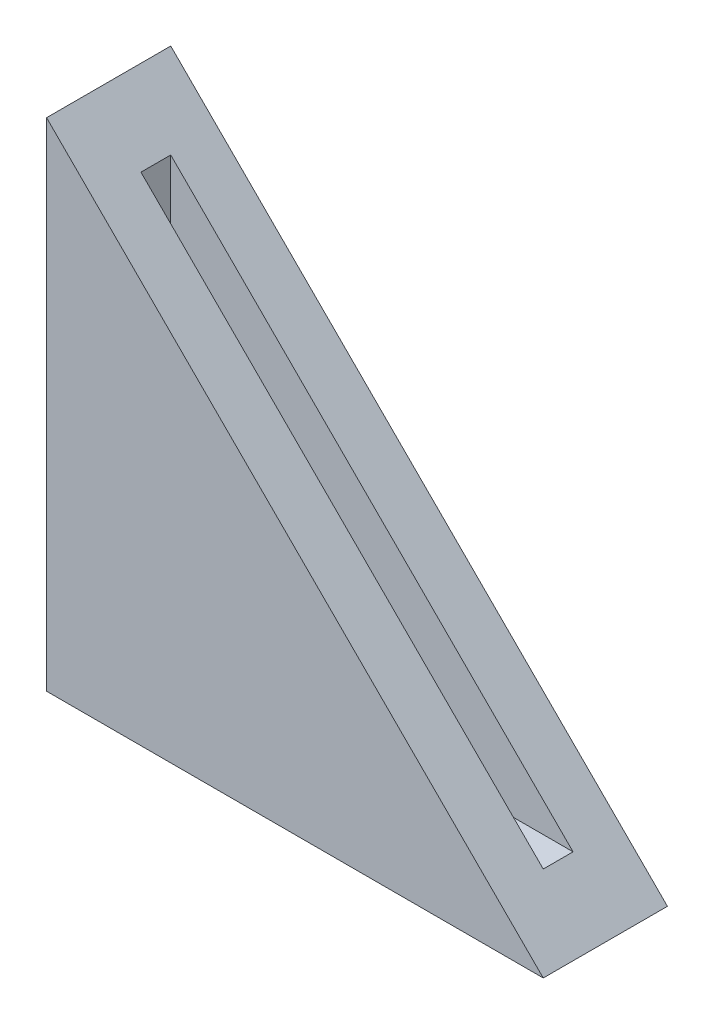
SolidWorks part; units mm, degrees
ref_plane "Plan de face" through (0, 0, 0) normal (0, 0, 1) x (1, 0, 0)
ref_plane "Plan de dessus" through (0, 0, 0) normal (0, 1, 0) x (1, 0, 0)
ref_plane "Plan de droite" through (0, 0, 0) normal (1, 0, 0) x (0, 0, -1)
sketch "Esquisse1" plane through (0, 0, 0) normal (0, 0, 1) x (1, 0, 0)
  line L0 (0, 0) -> (0, 60)
  line L1 (0, 0) -> (60, 0)
  line L2 (0, 60) -> (60, 0)
extrude "Boss.-Extru.1" add sketch "Esquisse1" along normal blind 7.5
sketch "Esquisse4" plane through (0, 0, 0) normal (0, 0, -1) x (-1, 0, 0)
  line L3 (-60, 0) -> (0, 0)
  line L4 (0, 0) -> (0, 60)
  line L5 (0, 60) -> (-60, 0)
  line L6 (-60, 0) -> (0, 0)
  line L7 (0, 0) -> (0, 60)
  line L8 (0, 60) -> (-60, 0)
  dimension "D1" = 0
extrude "Boss.-Extru.2" add sketch "Esquisse4" along normal blind 7.5
sketch "Esquisse5" plane through (0, 0, 0) normal (0, 0, 1) x (1, 0, 0)
  line L0 (19.7999, 5.7) -> (65.4107, 5.7)
  line L1 (60, 0) -> (0, 0) construction
  line L2 (65.4107, 5.7) -> (5.7, 61.2809)
  line L3 (0, 0) -> (0, 60) construction
  line L4 (5.7, 19.9891) -> (5.7, 5.7)
  line L5 (5.7, 5.7) -> (19.7999, 5.7)
  line L9 (5.7, 61.2809) -> (5.7, 19.9891)
  dimension "D1" = 5.7
  dimension "D2" = 5.7
extrude "Enlèv. mat.-Extru.1" cut sketch "Esquisse5" against normal blind 1.8 and the other way blind 1.8
